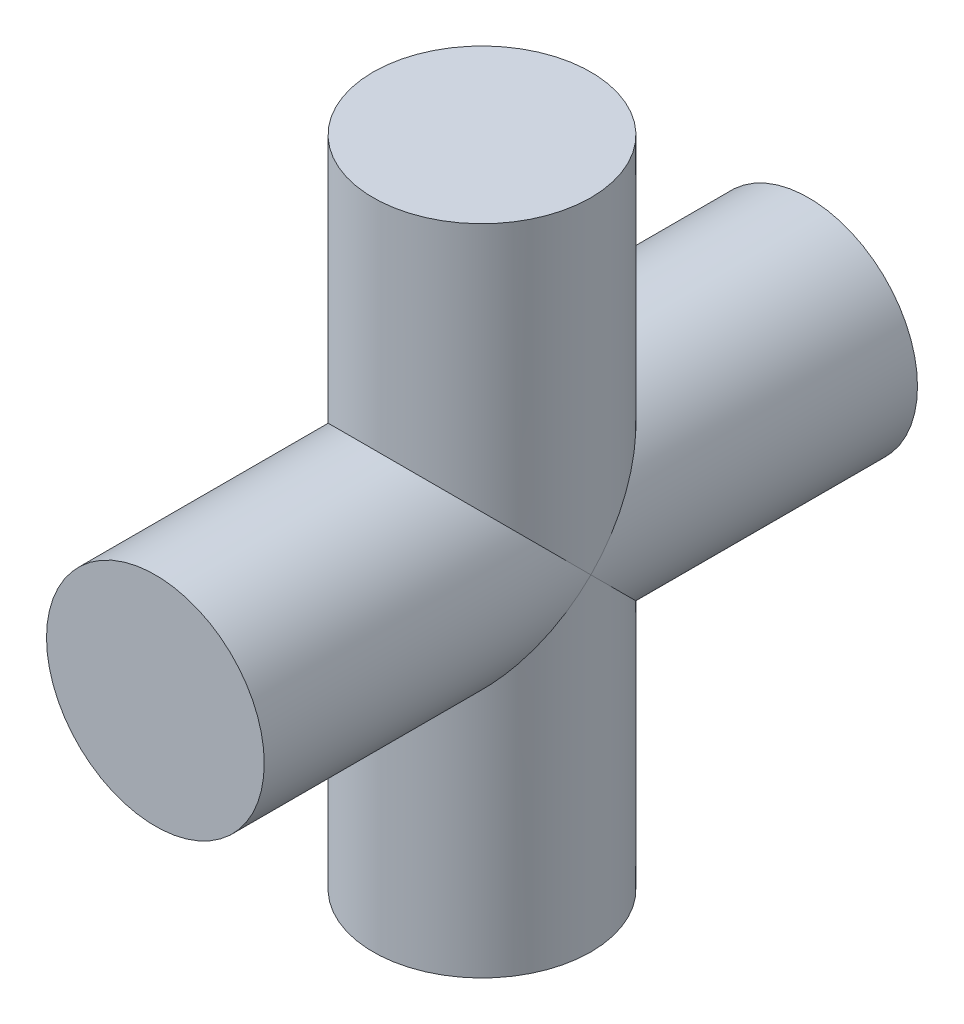
SolidWorks part; units mm, degrees
ref_plane "Płaszczyzna przednia" through (0, 0, 0) normal (0, 0, 1) x (1, 0, 0)
ref_plane "Płaszczyzna górna" through (0, 0, 0) normal (0, 1, 0) x (1, 0, 0)
ref_plane "Płaszczyzna prawa" through (0, 0, 0) normal (1, 0, 0) x (0, 0, -1)
sketch "Szkic1" plane through (0, 0, 0) normal (0, 0, 1) x (1, 0, 0)
  line L1 (0, 33) -> (-11, 33)
  line L2 (0, 33) -> (0, -33)
  line L3 (0, -33) -> (-11, -33)
  line L4 (-11, 33) -> (-11, -33)
  point P4 (0, 0)
  dimension "D1" = 66
  dimension "D2" = 11
revolve "Obrót1" add sketch "Szkic1" angle 360 about L2
sketch "Szkic2" plane through (0, 0, 0) normal (0, 1, 0) x (1, 0, 0)
  line L1 (-11, 33) -> (0, 33)
  line L2 (-11, 33) -> (-11, -33)
  line L3 (-11, -33) -> (0, -33)
  line L4 (0, 33) -> (0, -33)
  point P4 (0, 0)
  dimension "D1" = 66
  dimension "D2" = 11
revolve "Obrót2" add sketch "Szkic2" angle 360 about L4
